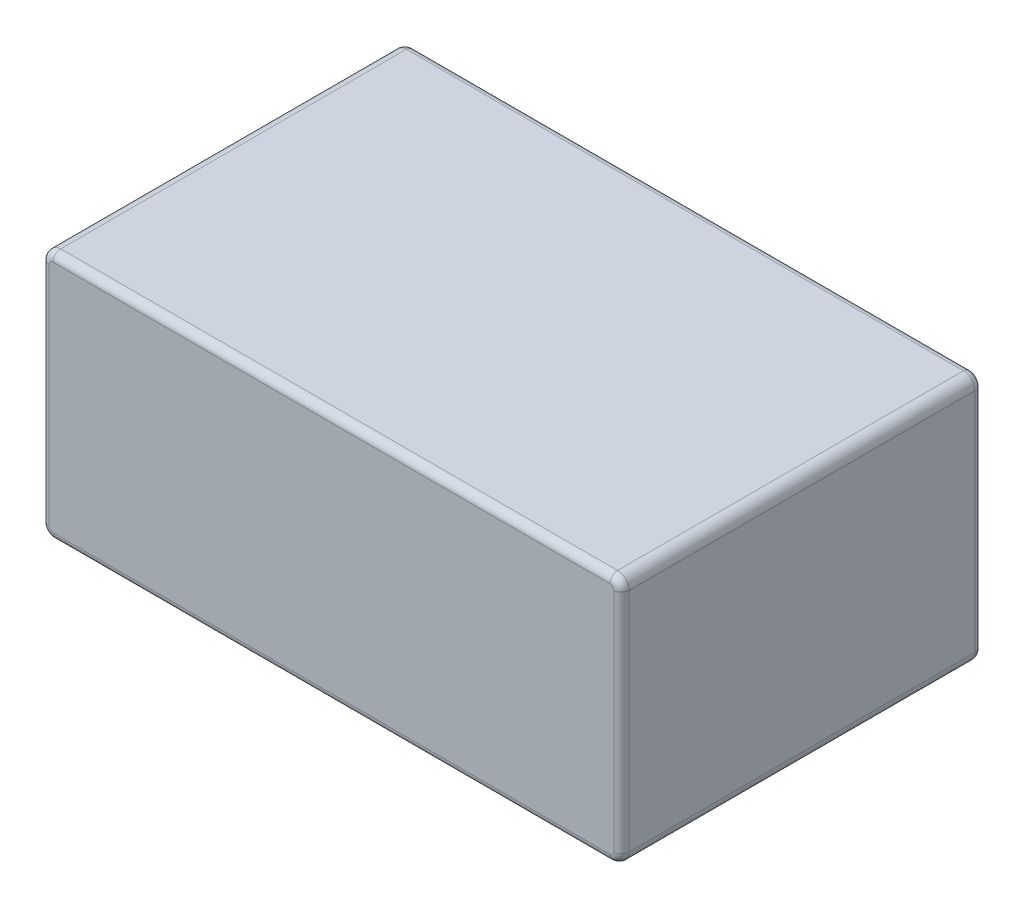
SolidWorks part; units mm, degrees
ref_plane "Front Plane" through (0, 0, 0) normal (0, 0, 1) x (1, 0, 0)
ref_plane "Top Plane" through (0, 0, 0) normal (0, 1, 0) x (1, 0, 0)
ref_plane "Right Plane" through (0, 0, 0) normal (1, 0, 0) x (0, 0, -1)
sketch "Block sketch 1" plane through (0, 0, 0) normal (0, 0, 1) x (1, 0, 0)
  line L0 (370, -112.5) -> (515, -112.5)
  line L1 (518, -109.5) -> (518, -50.5)
  line L2 (515, -47.5) -> (370, -47.5)
  line L3 (367, -50.5) -> (367, -109.5)
  arc A0 (515, -112.5) -> (518, -109.5) centre (515, -109.5) ccw
  arc A1 (518, -50.5) -> (515, -47.5) centre (515, -50.5) ccw
  arc A2 (370, -47.5) -> (367, -50.5) centre (370, -50.5) ccw
  arc A3 (367, -109.5) -> (370, -112.5) centre (370, -109.5) ccw
  dimension "D1" = 3
  dimension "D2" = 151
  dimension "D3" = 65
extrude "Block 1" add sketch "Block sketch 1" along normal blind 94 from offset 323 separate body
fillet "Block edge fillet 1" radius 2 16 edges at (367.8787, -111.6213, 417) (367.8787, -48.3787, 417) (517.1213, -48.3787, 417) (517.1213, -111.6213, 417) (517.1213, -48.3787, 323) (517.1213, -111.6213, 323) (442.5, -112.5, 323) (367.8787, -111.6213, 323) (367, -80, 323) (367.8787, -48.3787, 323) (518, -80, 417) (367, -80, 417) (442.5, -47.5, 417) (442.5, -112.5, 417) (518, -80, 323) (442.5, -47.5, 323)
